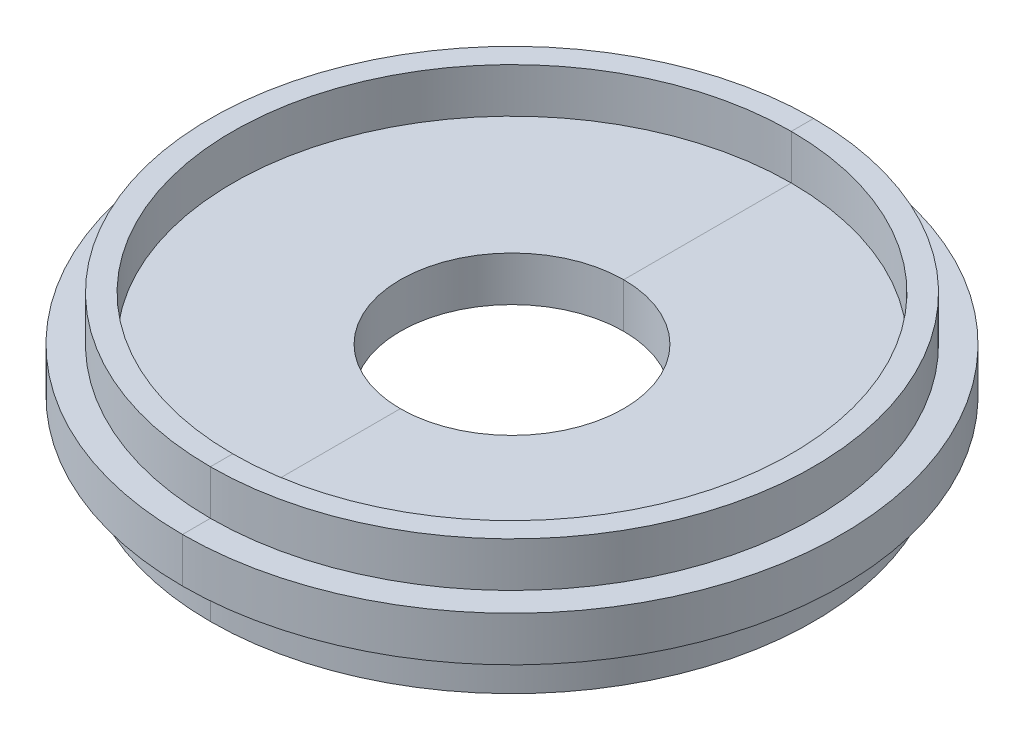
SolidWorks part; units mm, degrees
material "6061-T6 (SS)"
ref_plane "Front Plane" through (0, 0, 0) normal (0, 0, 1) x (1, 0, 0)
ref_plane "Top Plane" through (0, 0, 0) normal (0, 1, 0) x (1, 0, 0)
ref_plane "Right Plane" through (0, 0, 0) normal (1, 0, 0) x (0, 0, -1)
sketch "Sketch1" plane through (0, 0, 0) normal (0, 1, 0) x (1, 0, 0)
  circle A0 centre (0, 0) radius 93.6625
  circle A1 centre (0, 0) radius 31.75
  dimension "D1" = 187.325
  dimension "D2" = 63.5
extrude "Boss-Extrude1" add sketch "Sketch1" along normal mid plane 12.7
sketch "Sketch5" plane through (0, 6.35, 0) normal (0, 1, 0) x (1, 0, 0)
  circle A0 centre (0, 0) radius 85.725
  circle A1 centre (0, 0) radius 79.375
  dimension "D1" = 171.45
  dimension "D2" = 158.75
extrude "Boss-Extrude2" add sketch "Sketch5" along normal blind 12.7
ref_plane "Plane1" through (0, 0, -85.725) normal (0, 0, -1) x (-1, 0, 0)
sketch "Sketch6" plane through (0, 0, -85.725) normal (0, 0, -1) x (-1, 0, 0)
  line L0 (0, 55) -> (0, -55) construction
  line L1 (93.6625, 6.35) -> (-93.6625, 6.35) construction
  circle A0 centre (0, 12.7) radius 1.4351
  dimension "D1" = 2.8702
  dimension "D2" = 6.35
extrude "Cut-Extrude1" [suppressed] cut sketch "Sketch6" against normal blind 12.7
pattern_circular "CirPattern1" [suppressed] count 12 over 360
mirror "Mirror1" about plane through (0, 0, 0) normal (0, 1, 0) of "CirPattern1", "Cut-Extrude1", "Boss-Extrude2"
sketch "Sketch7" plane through (0, 19.05, 0) normal (0, 1, 0) x (1, 0, 0)
  line L0 (-25.7878, 75.0692) -> (-28.1663, 80.9657)
  line L1 (28.1663, 80.9657) -> (25.7878, 75.0692)
  arc A0 (28.1663, 80.9657) -> (-28.1663, 80.9657) centre (0, 0) ccw
  circle A1 centre (0, 0) radius 85.725 construction
  arc A2 (25.7878, 75.0692) -> (-25.7878, 75.0692) centre (0, 0) ccw
  circle A3 centre (0, 0) radius 79.375 construction
extrude "Boss-Extrude3" add sketch "Sketch7" against normal up to surface (25.4 mm away)
mirror "Mirror3" about plane through (0, 0, 0) normal (0, 1, 0) of "Boss-Extrude3"
mirror "Mirror4" about plane through (0, 0, 0) normal (0, 0, 1) of "Boss-Extrude3"
mirror "Mirror5" about plane through (0, 0, 0) normal (0, 1, 0) of "Mirror4"
sketch "Sketch4" plane through (0, 0, 0) normal (0, 0, 1) x (1, 0, 0)
  line L0 (0, 23.2786) -> (0, -14.9525) construction
sketch "Sketch3" plane through (0, 0, 0) normal (0, 0, 1) x (1, 0, 0)
  line L0 (-31.75, -6.35) -> (-56.6752, 6.35)
  line L1 (93.6625, 6.35) -> (-93.6625, 6.35) construction
  line L2 (-56.6752, 6.35) -> (-31.75, 6.35)
  line L3 (-31.75, 6.35) -> (-31.75, -6.35)
  line L4 (-31.75, -6.35) -> (31.75, -6.35) construction
  line L5 (31.75, 6.35) -> (-31.75, 6.35) construction
  dimension "D1" = 27
revolve "Cut-Revolve1" [suppressed] cut sketch "Sketch3" angle 360 about L0
split "Split1" trim tools "Right Plane" bodies to split 114 resulting bodies 104 105
